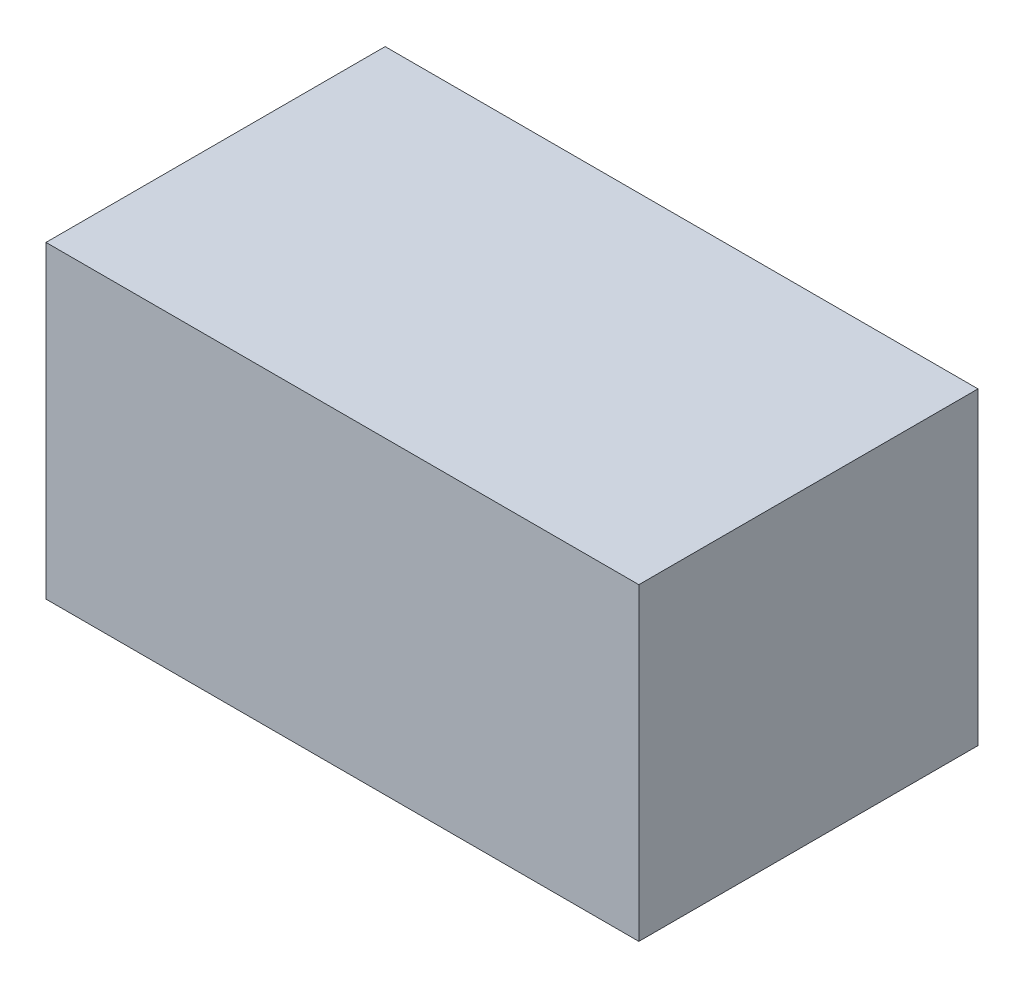
SolidWorks part; units mm, degrees
ref_plane "Front Plane" through (0, 0, 0) normal (0, 0, 1) x (1, 0, 0)
ref_plane "Top Plane" through (0, 0, 0) normal (0, 1, 0) x (1, 0, 0)
ref_plane "Right Plane" through (0, 0, 0) normal (1, 0, 0) x (0, 0, -1)
sketch "Sketch2" plane through (0, 0, 0) normal (0, 1, 0) x (1, 0, 0)
  line L2 (-41.1232, 16.9815) -> (27.5768, 16.9815)
  line L3 (-41.1232, 16.9815) -> (-41.1232, -22.3185)
  line L4 (-41.1232, -22.3185) -> (27.5768, -22.3185)
  line L5 (27.5768, 16.9815) -> (27.5768, -22.3185)
  dimension "D1" = 68.7
  dimension "D2" = 39.3
extrude "Boss-Extrude1" add sketch "Sketch2" along normal blind 35.8 contours L3 L4 L5 L2
